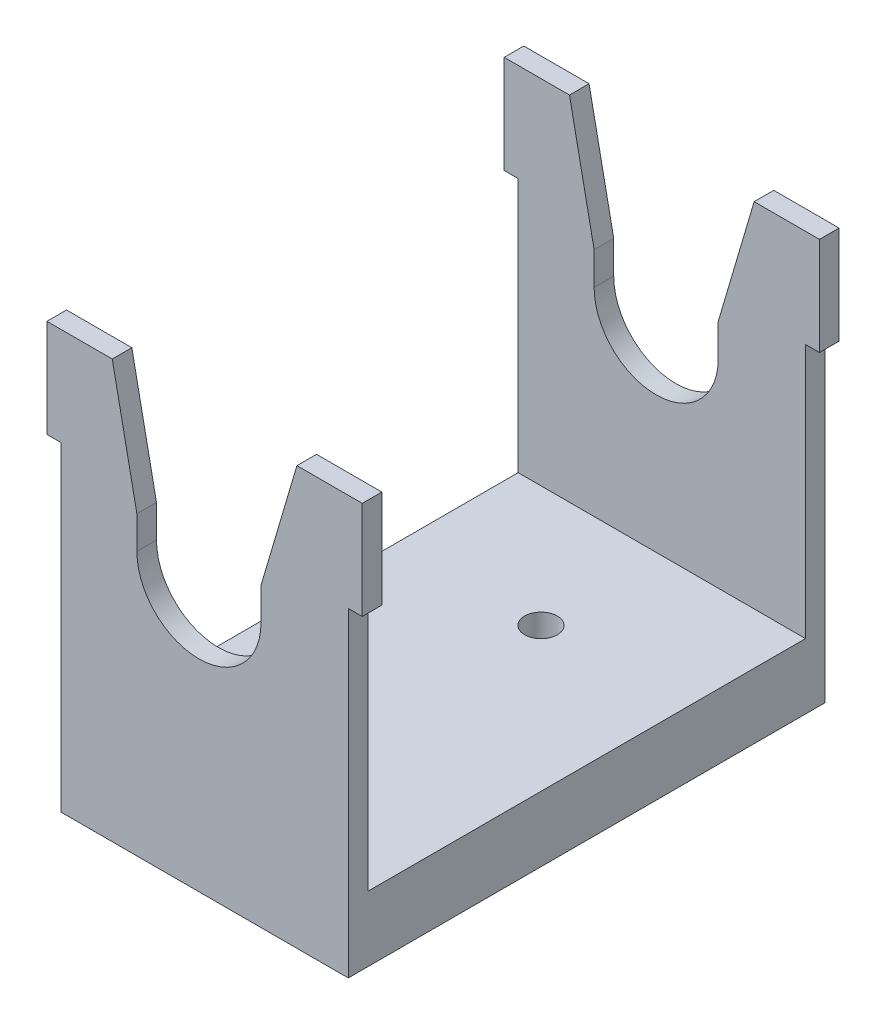
SolidWorks part; units mm, degrees
material "1.4016 (X6Cr17)"
ref_plane "Front Plane" through (0, 0, 0) normal (0, 0, 1) x (1, 0, 0)
ref_plane "Top Plane" through (0, 0, 0) normal (0, 1, 0) x (1, 0, 0)
ref_plane "Right Plane" through (0, 0, 0) normal (1, 0, 0) x (0, 0, -1)
sketch "Sketch1" plane through (0, 0, 0) normal (0, 0, 1) x (1, 0, 0)
  line L0 (-11.2866, 0) -> (32.7134, 0)
  line L1 (32.7134, 0) -> (32.7134, 49)
  line L2 (32.7134, 49) -> (34.8496, 49)
  line L3 (34.8496, 49) -> (34.8496, 64)
  line L6 (-13.4228, 64) -> (-13.4228, 49)
  line L7 (-13.4228, 49) -> (-11.2866, 49)
  line L8 (-11.2866, 49) -> (-11.2866, 0)
  line L9 (34.8496, 64) -> (24.8496, 64)
  line L11 (-13.4228, 64) -> (-3.4228, 64)
  line L13 (9.8496, 146.4208) -> (9.8496, -112.4084) construction
  line L14 (19.3496, 45.3783) -> (19.3496, 40.3783)
  line L15 (0.3496, 45.3783) -> (0.3496, 40.3783)
  line L16 (0.3496, 45.3783) -> (-3.4228, 64)
  line L17 (19.3496, 45.3783) -> (24.8496, 64)
  arc A1 (19.3496, 40.3783) -> (0.3496, 40.3783) centre (9.8496, 40.3783) cw
  dimension "D1" = 9.5
  dimension "D2" = 25
  dimension "D3" = 44
  dimension "D4" = 10
  dimension "D5" = 2.1362
  dimension "D6" = 64
  dimension "D7" = 15
  dimension "D8" = 0
  dimension "D9" = 5
  dimension "D10" = 19
extrude "Boss-Extrude2" add sketch "Sketch1" along normal blind 3
sketch "Sketch2" plane through (0, 0, 0) normal (0, 1, 0) x (1, 0, 0)
  line L0 (-11.2866, -3) -> (-11.2866, 0) construction
  line L5 (32.7134, 0) -> (-11.2866, 0)
  line L6 (32.7134, 0) -> (32.7134, 70)
  line L7 (32.7134, 70) -> (-11.2866, 70)
  line L8 (-11.2866, 0) -> (-11.2866, 70)
  line L9 (32.7134, -3) -> (32.7134, 0) construction
  dimension "D1" = 44
  dimension "D2" = 70
extrude "Boss-Extrude3" add sketch "Sketch2" along normal blind 10 contours L7 L8 L5 L6
ref_plane "Plane1" through (0, 0, -70) normal (0, 0, 1) x (1, 0, 0)
sketch "Sketch4" plane through (0, 0, -70) normal (0, 0, 1) x (1, 0, 0)
  line L13 (34.8496, 64) -> (24.8496, 64)
  line L14 (34.8496, 49) -> (34.8496, 64)
  line L15 (32.7134, 49) -> (34.8496, 49)
  line L16 (32.7134, 0) -> (32.7134, 49)
  line L17 (-11.2866, 0) -> (32.7134, 0)
  line L18 (-11.2866, 49) -> (-11.2866, 0)
  line L19 (-13.4228, 49) -> (-11.2866, 49)
  line L20 (-13.4228, 64) -> (-13.4228, 49)
  line L21 (-3.4228, 64) -> (-13.4228, 64)
  line L22 (0.3496, 45.3783) -> (-3.4228, 64)
  line L23 (0.3496, 40.3783) -> (0.3496, 45.3783)
  line L24 (19.3496, 45.3783) -> (19.3496, 40.3783)
  line L25 (24.8496, 64) -> (19.3496, 45.3783)
  line L26 (34.8496, 64) -> (24.8496, 64)
  line L27 (34.8496, 49) -> (34.8496, 64)
  line L28 (32.7134, 49) -> (34.8496, 49)
  line L29 (32.7134, 0) -> (32.7134, 49)
  line L30 (-11.2866, 0) -> (32.7134, 0)
  line L31 (-11.2866, 49) -> (-11.2866, 0)
  line L32 (-13.4228, 49) -> (-11.2866, 49)
  line L33 (-13.4228, 64) -> (-13.4228, 49)
  line L34 (-3.4228, 64) -> (-13.4228, 64)
  line L35 (0.3496, 45.3783) -> (-3.4228, 64)
  line L36 (0.3496, 40.3783) -> (0.3496, 45.3783)
  line L37 (19.3496, 45.3783) -> (19.3496, 40.3783)
  line L38 (24.8496, 64) -> (19.3496, 45.3783)
  arc A1 (0.3496, 40.3783) -> (19.3496, 40.3783) centre (9.8496, 40.3783) ccw
  arc A2 (0.3496, 40.3783) -> (19.3496, 40.3783) centre (9.8496, 40.3783) ccw
  dimension "D1" = 0
extrude "Boss-Extrude4" add sketch "Sketch4" along normal blind 3
sketch "Sketch7" plane through (0, 0, 0) normal (0, 1, 0) x (1, 0, 0)
  line L3 (-11.2866, 33.5) -> (32.7134, 33.5) construction
  line L4 (-11.2866, 0) -> (-11.2866, 67) construction
  line L5 (32.7134, 0) -> (32.7134, 67) construction
  circle A0 centre (10.7134, 48.5) radius 2.5
  circle A1 centre (10.7134, 18.5) radius 2.5
  point P18 (23.241, 13.1602)
  dimension "D1" = 5
  dimension "D2" = 15
  dimension "D3" = 15
  dimension "D4" = 22
  dimension "D5" = 22
extrude "Cut-Extrude1" cut sketch "Sketch7" along normal up to body separate body
